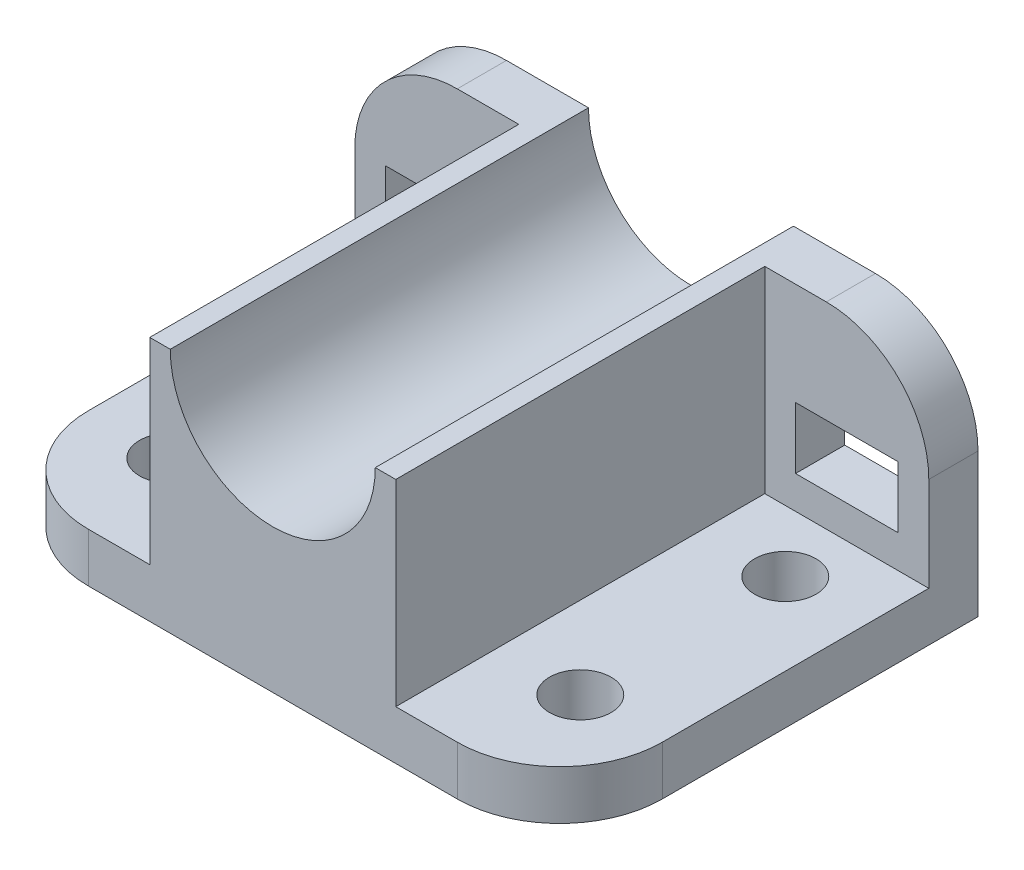
SolidWorks part; units mm, degrees
ref_plane "Front Plane" through (0, 0, 0) normal (0, 0, 1) x (1, 0, 0)
ref_plane "Top Plane" through (0, 0, 0) normal (0, 1, 0) x (1, 0, 0)
ref_plane "Right Plane" through (0, 0, 0) normal (1, 0, 0) x (0, 0, -1)
sketch "Sketch1" plane through (0, 0, 0) normal (0, 0, 1) x (1, 0, 0)
  line L0 (-70, 0) -> (70, 0)
  line L1 (70, 0) -> (70, 60)
  line L2 (70, 60) -> (25, 60)
  line L3 (-25, 60) -> (-70, 60)
  line L4 (-70, 60) -> (-70, 0)
  line L5 (0, 0) -> (0, 84.8606) construction
  arc A0 (25, 60) -> (-25, 60) centre (0, 60) cw
  point P10 (0, 0)
  dimension "D2" = 25
  dimension "D1" = 60
  dimension "D3" = 140
extrude "Boss-Extrude1" add sketch "Sketch1" along normal blind 102
sketch "Sketch2" plane through (0, 0, 102) normal (0, 0, 1) x (1, 0, 0)
  line L0 (70, 60) -> (25, 60) construction
  line L1 (30, 60) -> (70, 60)
  line L2 (30, 60) -> (30, 12)
  line L3 (30, 12) -> (70, 12)
  line L4 (70, 60) -> (70, 12)
  line L5 (70, 0) -> (70, 60) construction
  line L6 (-70, 0) -> (70, 0) construction
  dimension "D1" = 12
  dimension "D2" = 40
extrude "Cut-Extrude1" cut sketch "Sketch2" against normal blind 90
mirror "Mirror1" about plane through (0, 0, 0) normal (1, 0, 0) of "Cut-Extrude1"
fillet "Fillet1" radius 25 2 edges at (-70, 60, 6) (70, 60, 6)
fillet "Fillet2" radius 25 2 edges at (-70, 6, 102) (70, 6, 102)
sketch "Sketch3" plane through (0, 0, 12) normal (0, 0, 1) x (1, 0, 0)
  line L0 (45, 0) -> (70, 0) construction
  line L1 (37.5, 35) -> (62.5, 35)
  line L2 (37.5, 35) -> (37.5, 20)
  line L3 (37.5, 20) -> (62.5, 20)
  line L4 (62.5, 35) -> (62.5, 20)
  line L5 (30, 60) -> (30, 12) construction
  line L6 (70, 12) -> (70, 35) construction
  dimension "D1" = 15
  dimension "D2" = 35
  dimension "D3" = 7.5
  dimension "D4" = 7.5
extrude "Cut-Extrude2" cut sketch "Sketch3" against normal blind 90
mirror "Mirror2" about plane through (0, 0, 0) normal (1, 0, 0) of "Cut-Extrude2"
hole_wizard "Hole1" positions "Sketch4" profile "Sketch5" legacy end condition up to next
sketch "Sketch4" plane through (0, 12, 0) normal (0, 1, 0) x (1, 0, 0)
  line L0 (0, 0) -> (0, -133.9297) construction
  line L2 (-45, 0) -> (-70, 0) construction
  point P0 (50, -77)
  point P2 (50, -27)
  point P4 (-50, -27)
  point P6 (-50, -77)
  point P14 (0, 0)
  point P15 (0, 0)
  point P16 (0, 0)
  point P17 (-50.8076, -75.564)
  dimension "D1" = 50
  dimension "100" = 100
  dimension "D2" = 50
  dimension "D3" = 77
sketch "Sketch5" plane through (50, 12, 77) normal (1, 0, 0) x (0, 0, 1)
  line L0 (0, 0) -> (0, 12)
  line L1 (0, 12) -> (7.5, 12)
  line L2 (7.5, 12) -> (7.5, 0)
  line L3 (7.5, 0) -> (0, 0)
  line L4 (0, 110) -> (0, -10) construction
  dimension "Diameter" = 15
  dimension "Depth" = 12
